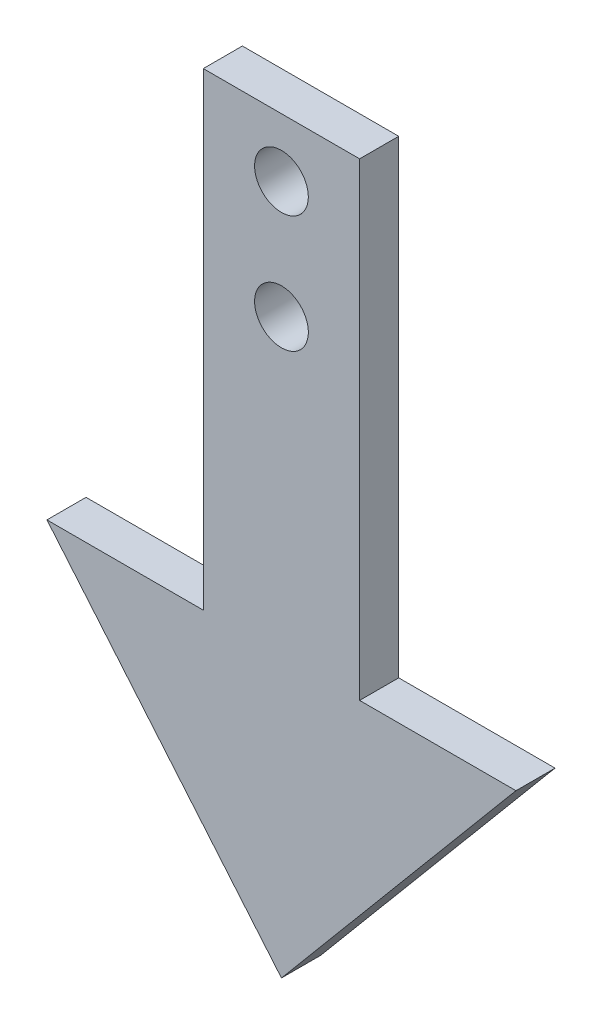
SolidWorks part; units mm, degrees
material "Acrylic (Medium-high impact)"
ref_plane "Front Plane" through (0, 0, 0) normal (0, 0, 1) x (1, 0, 0)
ref_plane "Top Plane" through (0, 0, 0) normal (0, 1, 0) x (1, 0, 0)
ref_plane "Right Plane" through (0, 0, 0) normal (1, 0, 0) x (0, 0, -1)
sketch "Sketch1" plane through (0, 0, 0) normal (0, 0, 1) x (1, 0, 0)
  line L0 (-6.35, -19.05) -> (-19.05, -19.05)
  line L1 (-6.35, 19.05) -> (6.35, 19.05)
  line L2 (-6.35, 19.05) -> (-6.35, -19.05)
  line L3 (0, 19.05) -> (0, -32.1399) construction
  line L4 (6.35, 19.05) -> (6.35, -19.05)
  line L5 (-6.35, 19.05) -> (6.35, -19.05) construction
  line L6 (-6.35, -19.05) -> (6.35, 19.05) construction
  line L7 (-19.05, -19.05) -> (0, -41.7529)
  line L8 (0, -41.7529) -> (19.05, -19.05)
  line L9 (6.35, -19.05) -> (19.05, -19.05)
  point P0 (0, 0)
  point P12 (0, -25.4)
  dimension "D1" = 12.7
  dimension "D2" = 38.1
  dimension "D3" = 50
  dimension "D4" = 12.7
  dimension "D5" = 12.7
extrude "Boss-Extrude1" add sketch "Sketch1" along normal blind 3.175
sketch "Sketch2" plane through (0, 0, 3.175) normal (0, 0, 1) x (1, 0, 0)
  line L1 (6.35, 19.05) -> (-6.35, 19.05) construction
  line L2 (-6.35, 9.525) -> (6.35, 9.525) construction
  line L3 (-6.35, 19.05) -> (-6.35, -19.05) construction
  line L4 (6.35, -19.05) -> (6.35, 19.05) construction
  line L5 (6.35, -19.05) -> (6.35, 19.05) construction
  circle A0 centre (0, 14.2875) radius 2.1828
  circle A1 centre (0, 4.7625) radius 2.1828
  point P15 (0, 0)
  dimension "D1" = 6.35
  dimension "D3" = 4.7625
  dimension "D4" = 4.3656
  dimension "D2" = 9.525
extrude "Cut-Extrude2" cut sketch "Sketch2" against normal through all
